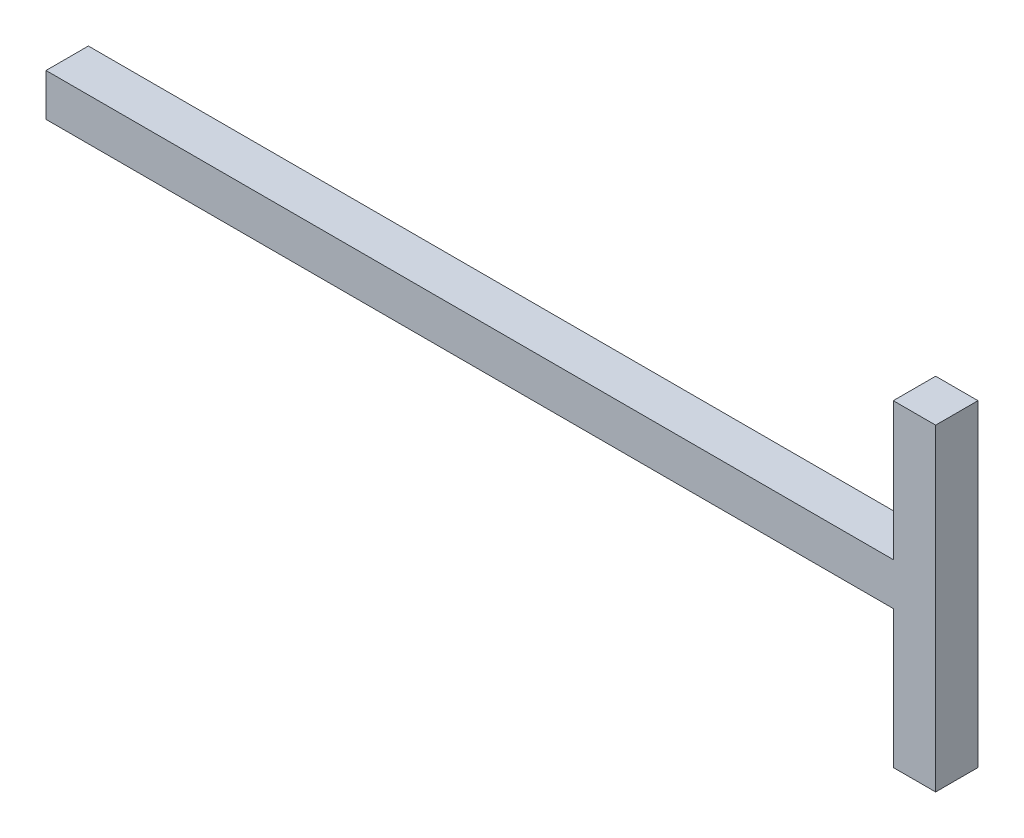
SolidWorks part; units mm, degrees
ref_plane "Front Plane" through (0, 0, 0) normal (0, 0, 1) x (1, 0, 0)
ref_plane "Top Plane" through (0, 0, 0) normal (0, 1, 0) x (1, 0, 0)
ref_plane "Right Plane" through (0, 0, 0) normal (1, 0, 0) x (0, 0, -1)
sketch "Sketch1" plane through (0, 0, 0) normal (0, 1, 0) x (1, 0, 0)
  line L1 (-10, 10) -> (10, 10)
  line L2 (-10, 10) -> (-10, -10)
  line L3 (-10, -10) -> (10, -10)
  line L4 (10, 10) -> (10, -10)
  line L5 (-10, 10) -> (10, -10) construction
  line L6 (-10, -10) -> (10, 10) construction
  point P0 (0, 0)
  dimension "D1" = 20
  dimension "D2" = 20
extrude "Boss-Extrude1" add sketch "Sketch1" along normal blind 150
sketch "Sketch2" plane through (-10, 0, 0) normal (-1, 0, 0) x (0, 0, 1)
  line L0 (-10, 150) -> (-10, 0) construction
  line L1 (-10, 85) -> (10, 85)
  line L2 (-10, 85) -> (-10, 65)
  line L3 (-10, 65) -> (10, 65)
  line L4 (10, 85) -> (10, 65)
  line L5 (10, 150) -> (10, 0) construction
  line L8 (-10, 150) -> (10, 150) construction
  line L10 (-10, 0) -> (10, 0) construction
  dimension "D1" = 20
  dimension "D2" = 65
  dimension "D3" = 65
extrude "Boss-Extrude2" add sketch "Sketch2" along normal blind 400
